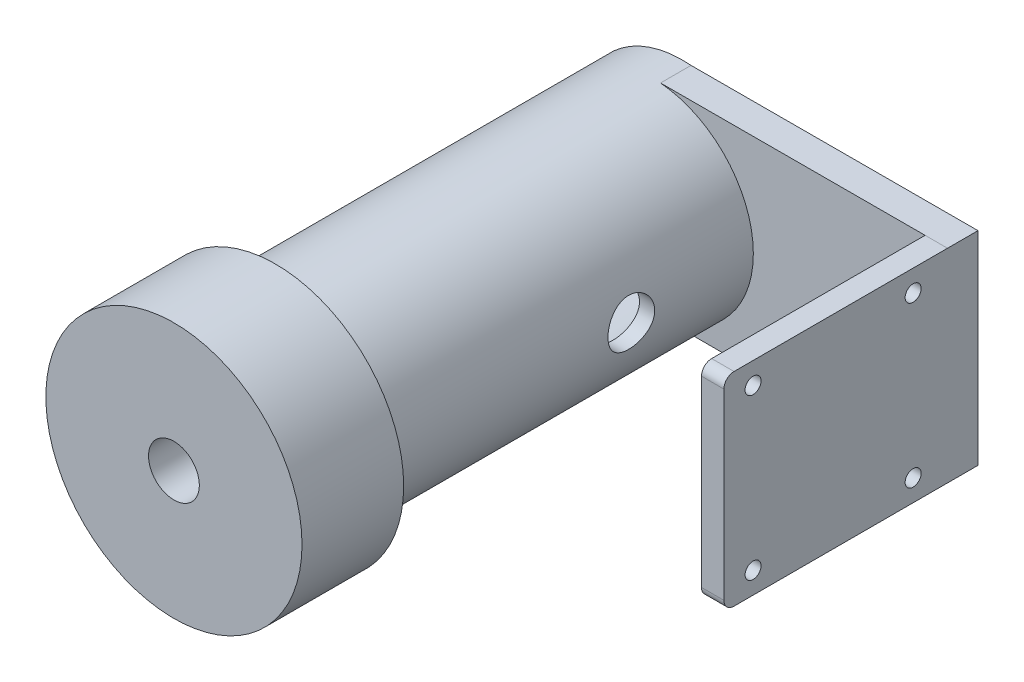
SolidWorks part; units mm, degrees
ref_plane "Front" through (0, 0, 0) normal (0, 0, 1) x (1, 0, 0)
ref_plane "Top" through (0, 0, 0) normal (0, 1, 0) x (1, 0, 0)
ref_plane "Right" through (0, 0, 0) normal (1, 0, 0) x (0, 0, -1)
sketch "Sketch3" plane through (0, 0, 0) normal (0, 0, 1) x (1, 0, 0)
  line L0 (0, -65.6804) -> (0, -71.4078) construction
  circle A0 centre (0, 0) radius 16.002
  dimension "D1" = 32.004
extrude "Boss-Extrude1" add sketch "Sketch3" along normal blind 12.7
sketch "Sketch5" plane through (0, 0, 0) normal (0, 0, -1) x (-1, 0, 0)
  line L1 (0, 6.4158) -> (-5.5563, 3.2079)
  line L2 (-5.5563, 3.2079) -> (-5.5563, -3.2079)
  line L3 (-5.5563, -3.2079) -> (0, -6.4158)
  line L4 (0, -6.4158) -> (5.5562, -3.2079)
  line L5 (5.5562, -3.2079) -> (5.5562, 3.2079)
  line L6 (5.5562, 3.2079) -> (0, 6.4158)
  dimension "D1" = 11.1125
sketch "Sketch4" plane through (0, 0, 0) normal (0, 0, -1) x (-1, 0, 0)
  circle A1 centre (0, 0) radius 12.7
  circle A2 centre (0, 0) radius 10.795
  dimension "D1" = 25.4
  dimension "D2" = 21.59
extrude "Boss-Extrude2" add sketch "Sketch4" along normal blind 50.8
ref_plane "Plane1" through (0, 0, -38.1) normal (0, 0, -1) x (-1, 0, 0)
sketch "Sketch9" plane through (0, 0, 0) normal (1, 0, 0) x (0, 0, -1)
  circle A0 centre (31.75, 0) radius 2.921
  dimension "D2" = 5.842
  dimension "D1" = 31.75
sketch "Sketch10" plane through (0, 0, 12.7) normal (0, 0, 1) x (1, 0, 0)
  circle A0 centre (0, 0) radius 3.175
  dimension "D1" = 6.35
extrude "Cut-Extrude1" cut sketch "Sketch9" against normal through all both and the other way through all
extrude "Cut-Extrude2" cut sketch "Sketch10" against normal through all and the other way through all
extrude "Cut-Extrude3" cut sketch "Sketch5" against normal blind 4.191
ref_plane "Plane2" through (0, 0, -46.99) normal (0, 0, 1) x (1, 0, 0)
sketch "Sketch12" plane through (0, 0, -46.99) normal (0, 0, 1) x (1, 0, 0)
  line L0 (-23.3152, 0) -> (-20.6579, 0) construction
  line L1 (36.9605, 12.7) -> (36.9605, -12.7)
  line L2 (36.9605, -12.7) -> (-1.1395, -12.6488)
  line L3 (36.9605, 12.7) -> (-1.1395, 12.6488)
  circle A0 centre (0, 0) radius 12.7 construction
  circle A1 centre (0, 0) radius 12.7
  circle A2 centre (0, 0) radius 12.7
  dimension "D1" = 38.1
extrude "Boss-Extrude3" add sketch "Sketch12" against normal up to surface (3.81 mm away) up to face at (-12.7, 0, -50.8)
sketch "Sketch13" plane through (0, 0, -46.99) normal (0, 0, 1) x (1, 0, 0)
  line L0 (36.9605, -12.7) -> (1.1055, -12.6518) construction
  line L1 (36.9605, 12.7) -> (34.1643, 12.7)
  line L2 (36.9605, 12.7) -> (36.9605, -12.6962)
  line L3 (36.9605, -12.6962) -> (34.1643, -12.6962)
  line L4 (34.1643, 12.7) -> (34.1643, -12.6962)
extrude "Boss-Extrude4" add sketch "Sketch13" along normal blind 27.94
sketch "Sketch14" plane through (34.1643, 0, 0) normal (-1, 0, 0) x (0, 0, 1)
  line L0 (-24.596, 0) -> (-32.6974, 0) construction
  line L1 (-32.6974, 0) -> (-32.6974, 18.8349) construction
  circle A1 centre (-22.6974, 10) radius 1
  circle A3 centre (-42.6974, 10) radius 1
  circle A4 centre (-42.6974, -10) radius 1
  circle A5 centre (-22.6974, -10) radius 1
  dimension "D1" = 2
  dimension "D2" = 10
  dimension "D3" = 10
extrude "Cut-Extrude4" cut sketch "Sketch14" against normal through all
fillet "Fillet1" radius 1.27 2 edges at (35.5624, -12.6962, -19.05) (35.5624, 12.7, -19.05)
